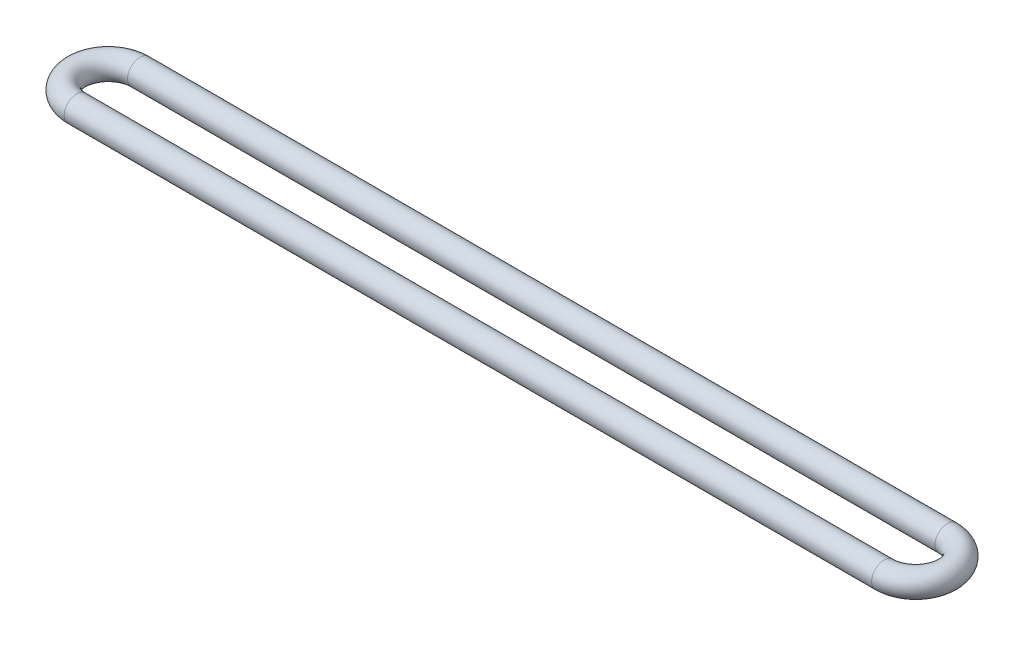
SolidWorks part; units mm, degrees
material "Natural Rubber"
ref_plane "Front" through (0, 0, 0) normal (0, 0, 1) x (1, 0, 0)
ref_plane "Top" through (0, 0, 0) normal (0, 1, 0) x (1, 0, 0)
ref_plane "Right" through (0, 0, 0) normal (1, 0, 0) x (0, 0, -1)
sketch "Sketch1" plane through (0, 0, 0) normal (0, 1, 0) x (1, 0, 0)
  line L0 (0, 0) -> (65, 0)
  line L1 (65, -5.1) -> (0, -5.1)
  arc A0 (65, 0) -> (65, -5.1) centre (65, -2.55) cw
  arc A1 (0, -5.1) -> (0, 0) centre (0, -2.55) cw
  dimension "D1" = 5.1
  dimension "D2" = 65
sketch "Sketch2" plane through (0, 0, 0) normal (1, 0, 0) x (0, 0, -1)
  circle A0 centre (0, 0) radius 1
  dimension "D1" = 2
sweep "Sweep1" add profiles "Sketch2" path "Sketch1"
